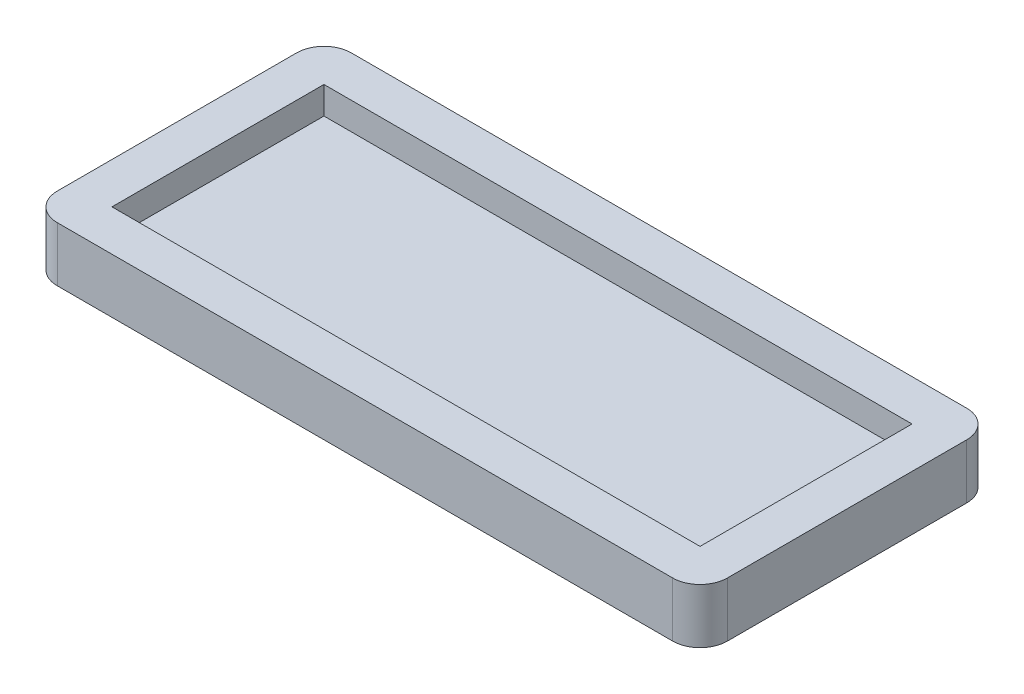
SolidWorks part; units mm, degrees
ref_plane "Alzado" through (0, 0, 0) normal (0, 0, 1) x (1, 0, 0)
ref_plane "Planta" through (0, 0, 0) normal (0, 1, 0) x (1, 0, 0)
ref_plane "Vista lateral" through (0, 0, 0) normal (1, 0, 0) x (0, 0, -1)
sketch "Croquis1" plane through (0, 0, 0) normal (0, 1, 0) x (1, 0, 0)
  line L0 (-24.5, 8.75) -> (-24.5, -8.75)
  line L1 (-21.5, 7.75) -> (21.5, 7.75)
  line L2 (-21.5, 7.75) -> (-21.5, -7.75)
  line L3 (-21.5, -7.75) -> (21.5, -7.75)
  line L4 (21.5, 7.75) -> (21.5, -7.75)
  line L5 (-22.5, -10.75) -> (22.5, -10.75)
  line L6 (24.5, 8.75) -> (24.5, -8.75)
  line L7 (-22.5, 10.75) -> (22.5, 10.75)
  line L8 (-24.5, 10.75) -> (-24.5, -10.75) construction
  line L9 (-24.5, -10.75) -> (24.5, -10.75) construction
  line L10 (24.5, 10.75) -> (24.5, -10.75) construction
  line L11 (-24.5, 10.75) -> (24.5, 10.75) construction
  arc A0 (-24.5, -8.75) -> (-22.5, -10.75) centre (-22.5, -8.75) ccw
  arc A1 (22.5, -10.75) -> (24.5, -8.75) centre (22.5, -8.75) ccw
  arc A2 (24.5, 8.75) -> (22.5, 10.75) centre (22.5, 8.75) ccw
  arc A3 (-24.5, 8.75) -> (-22.5, 10.75) centre (-22.5, 8.75) cw
  point P4 (0, -7.75)
  point P7 (21.5, 0)
  dimension "D4" = 2
  dimension "D1" = 43
  dimension "D2" = 15.5
  dimension "D3" = 3
extrude "Saliente-Extruir1" add sketch "Croquis1" along normal blind 2
sketch "Croquis2" plane through (0, 0, 0) normal (0, 1, 0) x (1, 0, 0)
  line L4 (-24.5, 8.75) -> (-24.5, -8.75)
  line L5 (22.5, 10.75) -> (-22.5, 10.75)
  line L6 (24.5, -8.75) -> (24.5, 8.75)
  line L7 (-22.5, -10.75) -> (22.5, -10.75)
  line L8 (-24.5, 8.75) -> (-24.5, -8.75)
  line L9 (22.5, 10.75) -> (-22.5, 10.75)
  line L10 (24.5, -8.75) -> (24.5, 8.75)
  line L11 (-22.5, -10.75) -> (22.5, -10.75)
  arc A4 (-24.5, -8.75) -> (-22.5, -10.75) centre (-22.5, -8.75) ccw
  arc A5 (-22.5, 10.75) -> (-24.5, 8.75) centre (-22.5, 8.75) ccw
  arc A6 (24.5, 8.75) -> (22.5, 10.75) centre (22.5, 8.75) ccw
  arc A7 (22.5, -10.75) -> (24.5, -8.75) centre (22.5, -8.75) ccw
  arc A8 (-24.5, -8.75) -> (-22.5, -10.75) centre (-22.5, -8.75) ccw
  arc A9 (-22.5, 10.75) -> (-24.5, 8.75) centre (-22.5, 8.75) ccw
  arc A10 (24.5, 8.75) -> (22.5, 10.75) centre (22.5, 8.75) ccw
  arc A11 (22.5, -10.75) -> (24.5, -8.75) centre (22.5, -8.75) ccw
  dimension "D1" = 0
extrude "Saliente-Extruir2" add sketch "Croquis2" against normal blind 2
